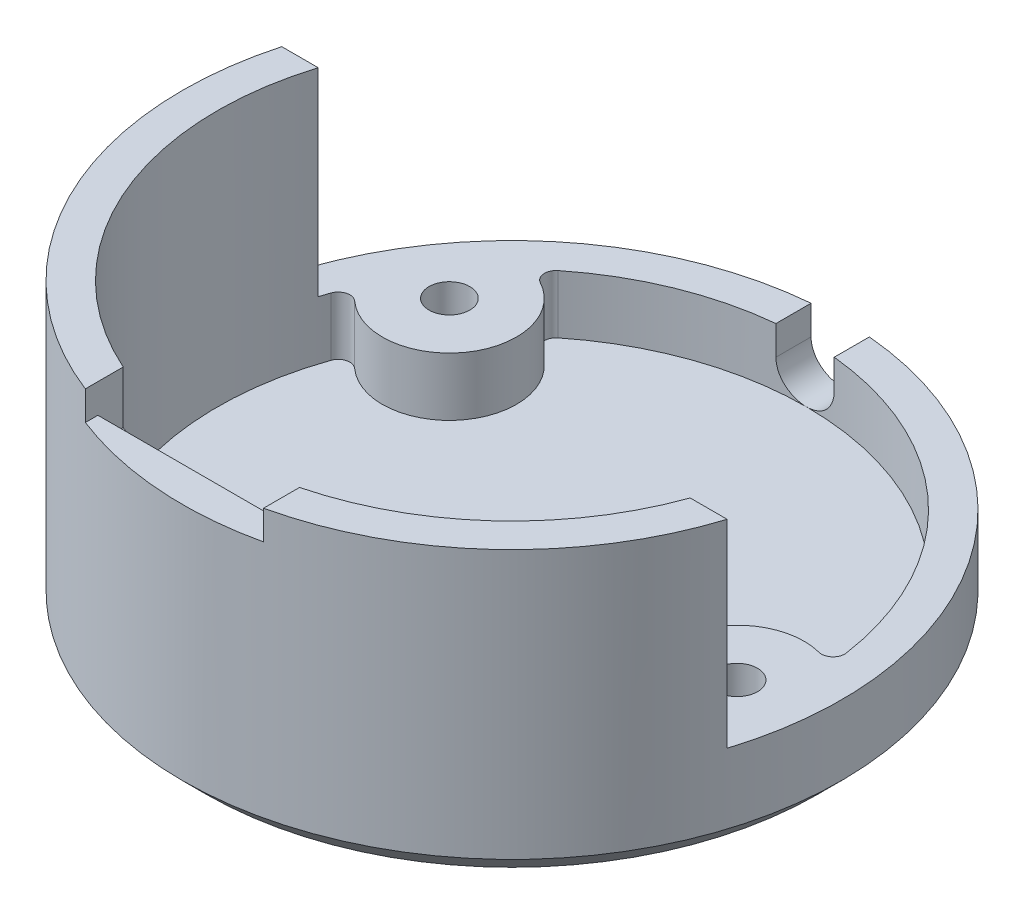
SolidWorks part; units mm, degrees
ref_plane "Front" through (0, 0, 0) normal (0, 0, 1) x (1, 0, 0)
ref_plane "Top" through (0, 0, 0) normal (0, 1, 0) x (1, 0, 0)
ref_plane "Right" through (0, 0, 0) normal (1, 0, 0) x (0, 0, -1)
sketch "Sketch1" plane through (0, 0, 0) normal (0, 1, 0) x (1, 0, 0)
  circle A0 centre (0, 0) radius 28.25
  dimension "D1" = 56.5
extrude "Boss-Extrude1" add sketch "Sketch1" along normal blind 25
shell "Shell1" thickness 3
sketch "Sketch2" plane through (0, 25, 0) normal (0, 1, 0) x (1, 0, 0)
  line L0 (0, 7.5) -> (-28.25, 7.5)
  line L1 (-28.25, 7.5) -> (-28.25, 28.25)
  line L2 (-28.25, 28.25) -> (28.25, 28.25)
  line L3 (28.25, 28.25) -> (28.25, -8.5)
  line L4 (28.25, -8.5) -> (0, -8.5)
  line L5 (0, -8.5) -> (0, 7.5)
  circle A0 centre (0, 0) radius 28.25 construction
  dimension "D1" = 7.5
  dimension "D2" = 8.5
extrude "Cut-Extrude1" cut sketch "Sketch2" against normal blind 17
sketch "Sketch3" plane through (0, 25, 0) normal (0, 1, 0) x (1, 0, 0)
  line L1 (-10.25, -28.25) -> (6.25, -28.25)
  line L2 (-10.25, -28.25) -> (-10.25, -23.076)
  line L3 (-10.25, -23.076) -> (6.25, -23.076)
  line L4 (6.25, -28.25) -> (6.25, -23.076)
  arc A1 (-27.2362, 7.5) -> (26.9409, -8.5) centre (0, 0) ccw construction
  arc A2 (-24.1104, 7.5) -> (23.7763, -8.5) centre (0, 0) ccw construction
  dimension "D1" = 16.5
  dimension "D2" = 6.25
extrude "Cut-Extrude2" cut sketch "Sketch3" against normal blind 2.5
sketch "Sketch5" plane through (0, 0, 0) normal (0, 0, 1) x (1, 0, 0)
  line L0 (2.5, 8) -> (2.5, 5.5)
  line L1 (28.25, 8) -> (-27.2362, 8) construction
  line L2 (25.25, 3) -> (-25.25, 3) construction
  line L3 (0, 3) -> (0, 8) construction
  line L4 (2.5, 8) -> (-2.5, 8)
  line L5 (-2.5, 8) -> (-2.5, 5.5)
  arc A0 (2.5, 5.5) -> (0, 3) centre (0, 5.5) cw
  arc A1 (-2.5, 5.5) -> (0, 3) centre (0, 5.5) ccw
  dimension "D1" = 5
extrude "Cut-Extrude3" cut sketch "Sketch5" against normal through all
sketch "Sketch6" plane through (0, 3, 0) normal (0, 1, 0) x (1, 0, 0)
  line L0 (-27.2362, 7.5) -> (-24.1104, 7.5) construction
  line L1 (23.7763, -8.5) -> (26.9409, -8.5) construction
  circle A0 centre (0, 0) radius 22.5 construction
  circle A1 centre (-18.3644, 13) radius 3.25
  circle A2 centre (22.2991, -3) radius 3.25
  dimension "D1" = 45
  dimension "D2" = 6.5
  dimension "D3" = 5.5
  dimension "D4" = 5.5
extrude "Cut-Extrude4" cut sketch "Sketch6" against normal through all
sketch "Sketch7" plane through (0, 3, 0) normal (0, 1, 0) x (1, 0, 0)
  circle A0 centre (-18.3644, 13) radius 1.75
  circle A1 centre (22.2991, -3) radius 1.75
  circle A2 centre (-18.3644, 13) radius 5.75
  arc A3 (-2.5, 28.1392) -> (-27.2362, 7.5) centre (0, 0) ccw construction
  circle A4 centre (22.2991, -3) radius 5.75
  arc A5 (26.9409, -8.5) -> (2.5, 28.1392) centre (0, 0) ccw construction
  dimension "D1" = 3.5
extrude "Boss-Extrude2" add sketch "Sketch7" along normal up to surface (5 mm away) up to face at (-15.5578, 8, -18.8477)
fillet "Fillet1" radius 1 4 edges at (23.7537, 5.5, 8.563) (25.1722, 5.5, -1.9808) (-17.073, 5.5, -18.6031) (-23.2198, 5.5, -9.9199)
chamfer "Chamfer1" distance 2 angle 45 1 edges at (0, 0, 28.25)
sketch "Sketch8" plane through (0, 22.5, 0) normal (0, 1, 0) x (1, 0, 0)
  line L0 (-10.25, -23.076) -> (-10.25, -26.3249) construction
  line L1 (-10.25, -23.076) -> (6.25, -23.076)
  line L2 (-10.25, -23.076) -> (-10.25, -25.25)
  line L3 (-10.25, -25.25) -> (6.25, -25.25)
  line L4 (6.25, -23.076) -> (6.25, -25.25)
  line L5 (6.25, -27.55) -> (6.25, -24.4643) construction
  arc A0 (-23.8381, 8.3252) -> (23.1195, -10.1514) centre (0, 0) ccw construction
  arc A1 (-10.25, -23.076) -> (6.25, -24.4643) centre (0, 0) ccw construction
  point P4 (0, 0)
  point P5 (-10.25, -23.076)
  point P6 (-9.2453, -26.0071)
  point P7 (0, 0)
  point P14 (-10.25, -25.2902)
  point P17 (6.25, -25.5241)
extrude "Cut-Extrude5" cut sketch "Sketch8" against normal blind 2
